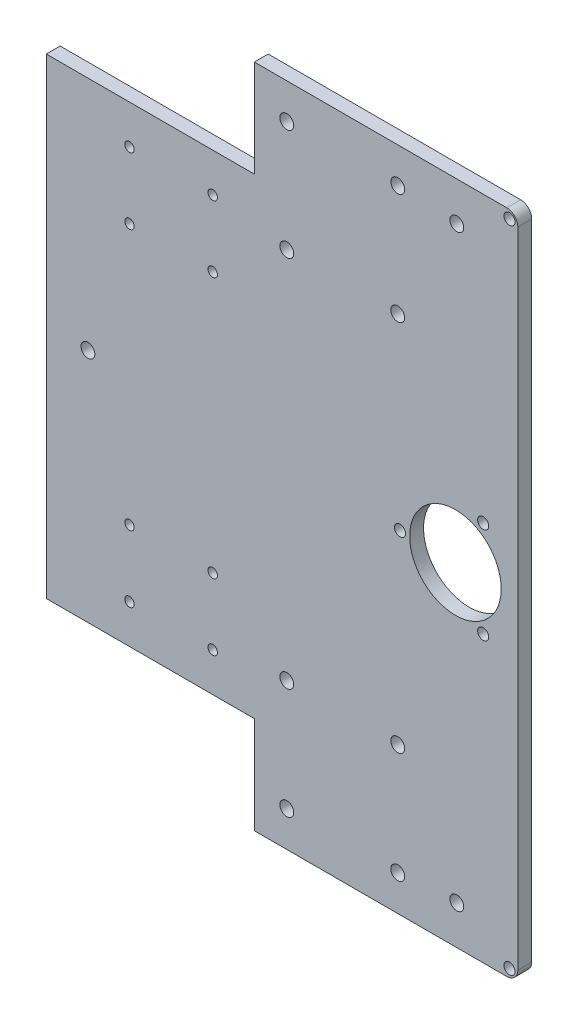
SolidWorks part; units mm, degrees
ref_plane "Front Plane" through (0, 0, 0) normal (0, 0, 1) x (1, 0, 0)
ref_plane "Top Plane" through (0, 0, 0) normal (0, 1, 0) x (1, 0, 0)
ref_plane "Right Plane" through (0, 0, 0) normal (1, 0, 0) x (0, 0, -1)
sketch "Sketch1" plane through (0, 0, 0) normal (0, 0, 1) x (1, 0, 0)
  line L1 (-85, 120) -> (85, 120)
  line L2 (-85, 120) -> (-85, -120)
  line L3 (-85, -120) -> (85, -120)
  line L4 (85, 120) -> (85, -120)
  line L5 (-85, 120) -> (85, -120) construction
  line L6 (-85, -120) -> (85, 120) construction
  point P0 (0, 0)
  dimension "D1" = 240
  dimension "D2" = 170
extrude "Boss-Extrude1" add sketch "Sketch1" along normal blind 5
sketch "Sketch2" plane through (0, 0, 5) normal (0, 0, 1) x (1, 0, 0)
  circle A0 centre (62.5, 0) radius 16.5
  dimension "D1" = 33
extrude "Cut-Extrude1" cut sketch "Sketch2" against normal through all
sketch "Sketch3" plane through (0, 0, 5) normal (0, 0, 1) x (1, 0, 0)
  circle A0 centre (72.5, -17.3205) radius 2
  circle A1 centre (72.5, 17.3205) radius 2
  circle A2 centre (42.5, 0) radius 2
extrude "Cut-Extrude2" cut sketch "Sketch3" against normal through all
sketch "Sketch4" plane through (0, 0, 5) normal (0, 0, 1) x (1, 0, 0)
  line L0 (55, 0) -> (-55, 0) construction
  circle A0 centre (-25, 47) radius 1.7
  circle A1 centre (-25, 71) radius 1.7
  circle A2 centre (-55, 47) radius 1.7
  circle A3 centre (-55, 71) radius 1.7
  circle A4 centre (-55, -71) radius 1.7
  circle A5 centre (-25, -71) radius 1.7
  circle A6 centre (-55, -47) radius 1.7
  circle A7 centre (-25, -47) radius 1.7
extrude "Cut-Extrude3" cut sketch "Sketch4" against normal through all
sketch "Sketch5" plane through (0, 0, 5) normal (0, 0, 1) x (1, 0, 0)
  line L0 (85, 120) -> (-85, 120) construction
  line L1 (-10, 120) -> (-85, 120)
  line L2 (-10, 120) -> (-10, 85)
  line L3 (-10, 85) -> (-85, 85)
  line L4 (-85, 120) -> (-85, 85)
  line L5 (-85, 120) -> (-85, -120) construction
  line L6 (55, 0) -> (-55, 0) construction
  line L7 (-10, -120) -> (-85, -120)
  line L8 (-85, -120) -> (-85, -85)
  line L9 (-10, -85) -> (-85, -85)
  line L10 (-10, -120) -> (-10, -85)
  dimension "D1" = 75
  dimension "D2" = 35
extrude "Cut-Extrude4" cut sketch "Sketch5" against normal through all
fillet "Fillet1" radius 4 1 edges at (85, -120, 2.5)
sketch "Sketch6" plane through (0, 0, 5) normal (0, 0, 1) x (1, 0, 0)
  circle A0 centre (82, -117) radius 2
  dimension "D1" = 4
extrude "Cut-Extrude5" cut sketch "Sketch6" against normal through all
mirror "Mirror5" about plane through (0, 0, 0) normal (0, 1, 0) of "Cut-Extrude5"
fillet "Fillet2" radius 4 1 edges at (85, 120, 2.5)
fillet "Fillet3" [suppressed] radius 4
sketch "Sketch7" plane through (0, 0, 5) normal (0, 0, 1) x (1, 0, 0)
  circle A0 centre (41.7, 107.25) radius 2.5
  circle A1 centre (41.7, 67.25) radius 2.5
  circle A2 centre (1.7, 67.25) radius 2.5
  circle A3 centre (1.7, 107.25) radius 2.5
  circle A4 centre (41.7, -107.25) radius 2.5
  circle A5 centre (1.7, -107.25) radius 2.5
  circle A6 centre (1.7, -67.25) radius 2.5
  circle A7 centre (41.7, -67.25) radius 2.5
  dimension "D1" = 5
extrude "Cut-Extrude6" cut sketch "Sketch7" against normal through all
sketch "Sketch8" plane through (0, 0, 0) normal (0, 0, -1) x (-1, 0, 0)
  circle A0 centre (-63, 106) radius 2.5
  circle A1 centre (-63, -106) radius 2.5
  circle A2 centre (70, 0) radius 2.5
  dimension "D1" = 5
extrude "Cut-Extrude7" cut sketch "Sketch8" against normal through all
